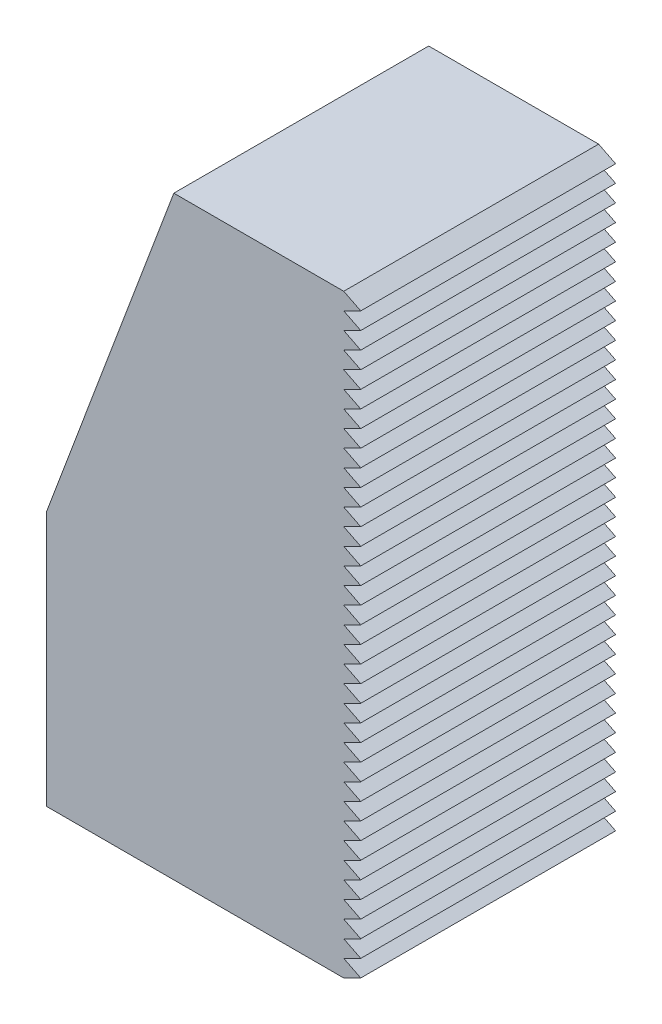
SolidWorks part; units mm, degrees
ref_plane "Front Plane" through (0, 0, 0) normal (0, 0, 1) x (1, 0, 0)
ref_plane "Top Plane" through (0, 0, 0) normal (0, 1, 0) x (1, 0, 0)
ref_plane "Right Plane" through (0, 0, 0) normal (1, 0, 0) x (0, 0, -1)
sketch "Sketch2" plane through (0, 0, 0) normal (0, 0, 1) x (1, 0, 0)
  line L0 (-35, 30) -> (-20, 70)
  line L1 (-20, 70) -> (0, 70)
  line L2 (0, 70) -> (0, 0)
  line L3 (0, 0) -> (-35, 0)
  line L4 (-35, 0) -> (-35, 30)
  point P2 (0, 0)
  dimension "D1" = 70
  dimension "D2" = 30
  dimension "D3" = 20
  dimension "D4" = 35
extrude "Boss-Extrude1" add sketch "Sketch2" along normal blind 30
sketch "Sketch3" plane through (0, 0, 30) normal (0, 0, 1) x (1, 0, 0)
  line L0 (0, 70) -> (2, 69)
  line L1 (2, 69) -> (0, 68)
  line L2 (0, 0) -> (0, 70) construction
  line L3 (0, 68) -> (0, 70)
  dimension "D1" = 2
  dimension "D2" = 2
extrude "Boss-Extrude3" add sketch "Sketch3" against normal up to surface (30 mm away) up to face at (-18, 34, 0)
pattern_linear "LPattern1" count 35 spacing 2 along (0, -1, 0) of "Boss-Extrude3"
